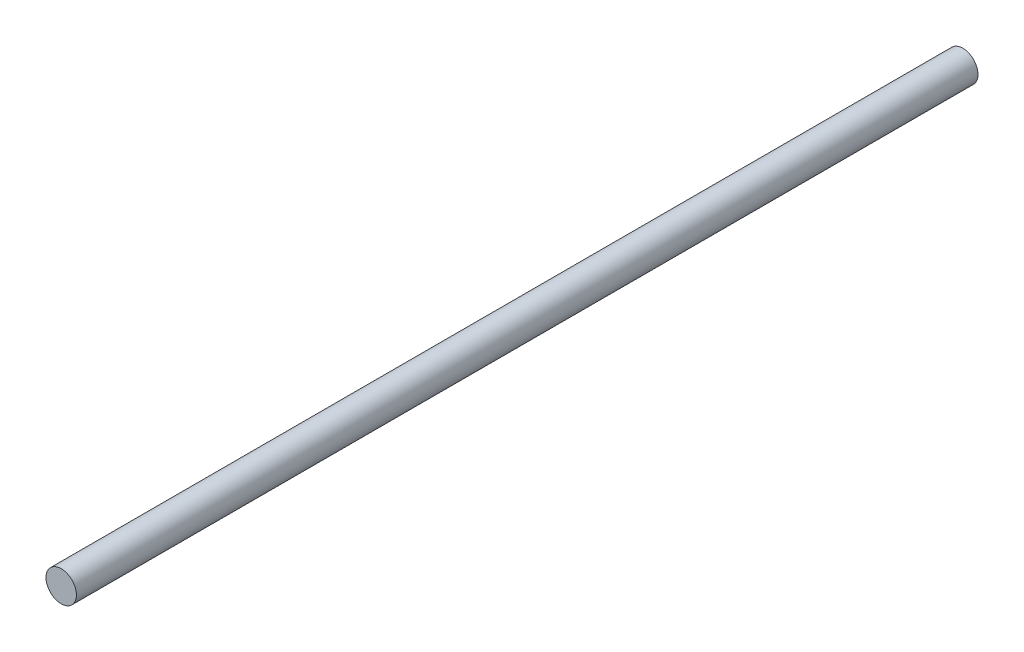
SolidWorks part; units mm, degrees
material "Acier allié inoxydable"
ref_plane "Plan de face" through (0, 0, 0) normal (0, 0, 1) x (1, 0, 0)
ref_plane "Plan de dessus" through (0, 0, 0) normal (0, 1, 0) x (1, 0, 0)
ref_plane "Plan de droite" through (0, 0, 0) normal (1, 0, 0) x (0, 0, -1)
sketch "Esquisse1" plane through (0, 0, 0) normal (0, 0, 1) x (1, 0, 0)
  circle A0 centre (0, 0) radius 4
  dimension "D1" = 8
extrude "Boss.-Extru.1" add sketch "Esquisse1" along normal blind 237
